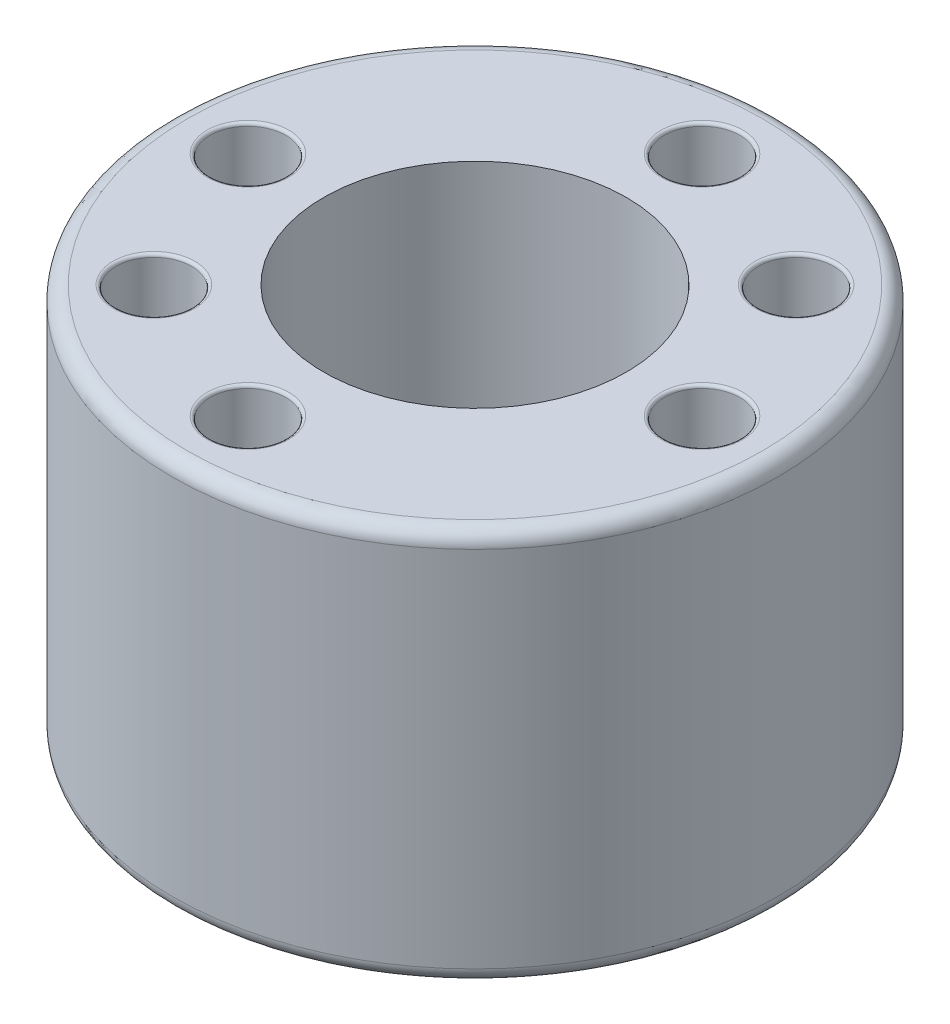
SolidWorks part; units mm, degrees
ref_plane "Front Plane" through (0, 0, 0) normal (0, 0, 1) x (1, 0, 0)
ref_plane "Top Plane" through (0, 0, 0) normal (0, 1, 0) x (1, 0, 0)
ref_plane "Right Plane" through (0, 0, 0) normal (1, 0, 0) x (0, 0, -1)
sketch "Sketch1" plane through (0, 0, 0) normal (0, 1, 0) x (1, 0, 0)
  circle A0 centre (0, 0) radius 10
  circle A1 centre (0, 0) radius 5
  dimension "D1" = 10
  dimension "D2" = 20
extrude "Boss-Extrude1" add sketch "Sketch1" along normal blind 13
sketch "Sketch2" plane through (0, 13, 0) normal (0, 1, 0) x (1, 0, 0)
  line L0 (0, 7.5) -> (0, 0) construction
  line L1 (0, 0) -> (5.3033, 5.3033) construction
  line L2 (-5.3033, 5.3033) -> (5.3033, -5.3033) construction
  circle A0 centre (0, 0) radius 7.5 construction
  circle A1 centre (0, 7.5) radius 1.25
  circle A2 centre (7.5, 0) radius 1.25
  circle A3 centre (0, -7.5) radius 1.25
  circle A4 centre (-7.5, 0) radius 1.25
  circle A5 centre (5.3033, 5.3033) radius 1.25
  circle A6 centre (-5.3033, -5.3033) radius 1.25
  point P14 (0, 0)
  dimension "D1" = 15
  dimension "D2" = 2.5
  dimension "D4" = 2.5
  dimension "D5" = 45
  dimension "D6" = 45
  dimension "D3" = 4
extrude "Cut-Extrude1" cut sketch "Sketch2" against normal blind 12
fillet "Fillet1" radius 0.5 2 edges at (0, 0, 10) (0, 13, 10)
fillet "Fillet2" radius 0.1 6 edges at (-5.3033, 13, 4.0533) (-7.5, 13, 1.25) (0, 13, 8.75) (7.5, 13, 1.25) (5.3033, 13, -4.0533) (0, 13, -6.25)
